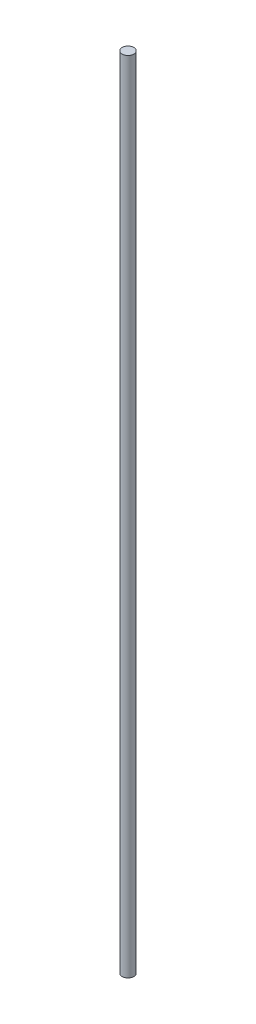
SolidWorks part; units mm, degrees
ref_plane "Front Plane" through (0, 0, 0) normal (0, 0, 1) x (1, 0, 0)
ref_plane "Top Plane" through (0, 0, 0) normal (0, 1, 0) x (1, 0, 0)
ref_plane "Right Plane" through (0, 0, 0) normal (1, 0, 0) x (0, 0, -1)
sketch "Sketch1" plane through (0, 0, 0) normal (0, 1, 0) x (1, 0, 0)
  circle A0 centre (0, 0) radius 2
  dimension "D1" = 4
extrude "Boss-Extrude1" add sketch "Sketch1" along normal blind 275
